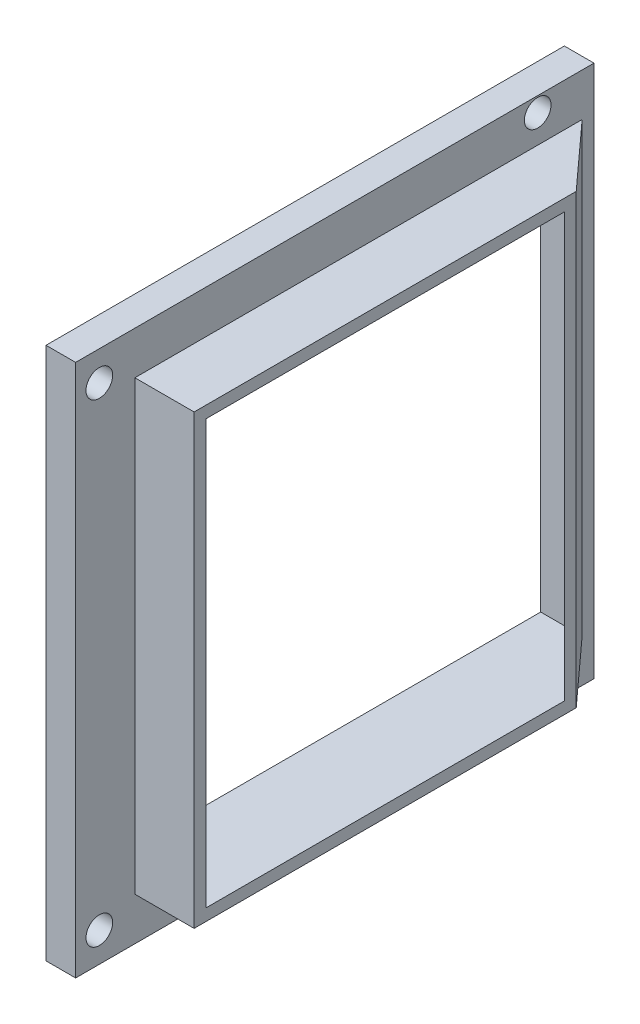
SolidWorks part; units mm, degrees
ref_plane "Front Plane" through (0, 0, 0) normal (0, 0, 1) x (1, 0, 0)
ref_plane "Top Plane" through (0, 0, 0) normal (0, 1, 0) x (1, 0, 0)
ref_plane "Right Plane" through (0, 0, 0) normal (1, 0, 0) x (0, 0, -1)
sketch "Sketch1" plane through (0, 0, 0) normal (1, 0, 0) x (0, 0, -1)
  line L1 (-43.75, -45) -> (43.75, -45)
  line L2 (-43.75, -45) -> (-43.75, 45)
  line L3 (-43.75, 45) -> (43.75, 45)
  line L4 (43.75, -45) -> (43.75, 45)
  line L5 (-43.75, -45) -> (43.75, 45) construction
  line L6 (-43.75, 45) -> (43.75, -45) construction
  line L7 (-31.75, -35.75) -> (39.75, -35.75)
  line L8 (-31.75, -35.75) -> (-31.75, 35.75)
  line L9 (-31.75, 35.75) -> (39.75, 35.75)
  line L10 (39.75, -35.75) -> (39.75, 35.75)
  line L11 (-31.75, -35.75) -> (39.75, 35.75) construction
  line L12 (-31.75, 35.75) -> (39.75, -35.75) construction
  point P0 (0, 0)
  point P6 (0, 0)
  point P11 (4, 0)
  dimension "D1" = 87.5
  dimension "D2" = 90
  dimension "D3" = 71.5
  dimension "D4" = 71.5
  dimension "D5" = 39.75
extrude "Boss-Extrude1" add sketch "Sketch1" along normal blind 5
hole_wizard "M4 Clearance Hole1" positions "Sketch2" profile "Sketch4" hole size "M4" standard "ANSI Metric"
sketch "Sketch2" plane through (5, 0, 0) normal (1, 0, 0) x (0, 0, -1)
  line L0 (43.75, 45) -> (-43.75, 45) construction
  line L1 (-43.75, 45) -> (-43.75, -45) construction
  line L2 (43.75, -45) -> (43.75, 45) construction
  point P0 (-39.75, 40)
  point P7 (34.25, 42.5)
  dimension "D1" = 5
  dimension "D2" = 4
  dimension "D3" = 2.5
  dimension "D4" = 9.5
sketch "Sketch4" plane through (5, 40, 39.75) normal (0, 1, 0) x (0, 0, -1)
  line L0 (0, 0) -> (0, 9.1519)
  line L1 (0, 9.1519) -> (2.25, 7.8)
  line L2 (2.25, 7.8) -> (2.25, 0)
  line L5 (2.25, 0) -> (0, 0)
  line L10 (0, 9.1519) -> (-2.25, 7.8) construction
  line L11 (0, -6.35) -> (0, 107.95) construction
  dimension "Hole Dia." = 4.5
  dimension "Hole Depth" = 7.8
  dimension "Drill Angle" = 118
mirror "Mirror1" about plane through (0, 0, 0) normal (0, 1, 0) of "M4 Clearance Hole1"
sketch "Sketch5" plane through (0, 45, 0) normal (0, 1, 0) x (1, 0, 0)
  line L0 (5, 39.75) -> (15, 28.75)
  line L1 (5, 43.75) -> (5, -43.75) construction
  line L2 (15, 28.75) -> (15, 30.75)
  line L3 (15, 30.75) -> (5, 41.75)
  line L5 (5, -31.75) -> (15, -31.75)
  line L6 (5, -31.75) -> (5, -33.75)
  line L7 (5, -33.75) -> (15, -33.75)
  line L8 (15, -31.75) -> (15, -33.75)
  line M3 (5, -43.75) -> (5, 43.75)
  dimension "D1" = 11
  dimension "D2" = 10
  dimension "D3" = 4
  dimension "D4" = 2
  dimension "D5" = 2
  dimension "D6" = 10
  dimension "D7" = 12
extrude "Boss-Extrude2" add sketch "Sketch5" against normal up to vertex (90 mm away) contours L8 L5 L7 M3 | L2 L3 L0 M3 up to point (5, -45, 43.75)
sketch "Sketch6" plane through (5, 0, 0) normal (1, 0, 0) x (0, 0, -1)
  line L0 (43.75, -45) -> (43.75, 45) construction
  line L1 (-43.75, 45) -> (43.75, 45)
  line L2 (-43.75, 45) -> (-43.75, 37.75)
  line L3 (-43.75, 37.75) -> (43.75, 37.75)
  line L4 (43.75, 45) -> (43.75, 37.75)
  line L7 (39.75, 35.75) -> (-31.75, 35.75) construction
  dimension "D1" = 2
extrude "Cut-Extrude1" cut sketch "Sketch6" along normal blind 10
sketch "Sketch8" plane through (0, 37.75, 0) normal (0, 1, 0) x (1, 0, 0)
  line L0 (15, 28.75) -> (15, -31.75)
  line L1 (15, -31.75) -> (5, -31.75)
  line L2 (5, -31.75) -> (5, 39.75)
  line L3 (5, 39.75) -> (15, 28.75)
extrude "Boss-Extrude3" add sketch "Sketch8" against normal blind 2
mirror "Mirror7" about plane through (0, 0, 0) normal (0, 1, 0) of "Boss-Extrude3", "Cut-Extrude1"
